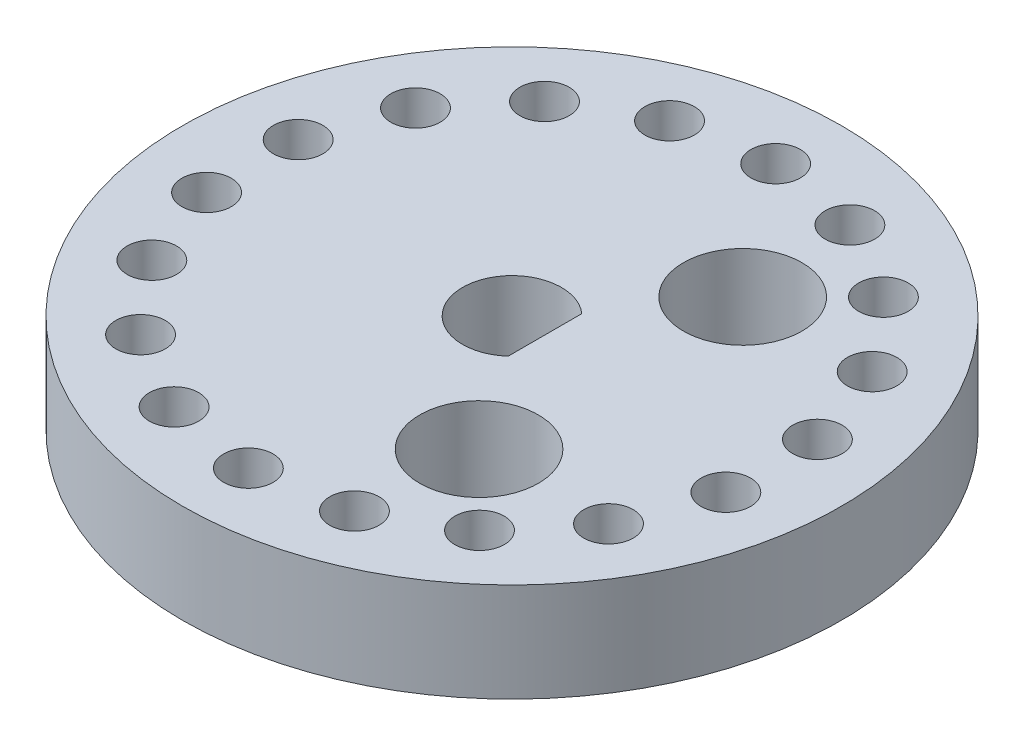
SolidWorks part; units mm, degrees
ref_plane "前视基准面" through (0, 0, 0) normal (0, 0, 1) x (1, 0, 0)
ref_plane "上视基准面" through (0, 0, 0) normal (0, 1, 0) x (1, 0, 0)
ref_plane "右视基准面" through (0, 0, 0) normal (1, 0, 0) x (0, 0, -1)
sketch "草图1" plane through (0, 0, 0) normal (0, 1, 0) x (1, 0, 0)
  circle A0 centre (0, 0) radius 10
extrude "凸台-拉伸1" add sketch "草图1" along normal blind 3
sketch "草图2" plane through (0, 3, 0) normal (0, 1, 0) x (1, 0, 0)
  line L0 (1, -1.118) -> (1, 1.118)
  line L20 (0, 0) -> (0, 1.25) construction
  arc A2 (1, -1.118) -> (1, 1.118) centre (0, 0) cw
  point P7 (0, 0)
  point P30 (0, 0)
sketch "草图3" plane through (0, 3, 0) normal (0, 1, 0) x (1, 0, 0)
  circle A19 centre (0, 0) radius 8 construction
  circle A39 centre (0, 8) radius 0.75
  circle A40 centre (2.7362, 7.5175) radius 0.75
  circle A63 centre (5.1423, 6.1284) radius 0.75
  circle A64 centre (6.9282, 4) radius 0.75
  circle A65 centre (7.8785, 1.3892) radius 0.75
  circle A66 centre (7.8785, -1.3892) radius 0.75
  circle A67 centre (6.9282, -4) radius 0.75
  circle A68 centre (5.1423, -6.1284) radius 0.75
  circle A69 centre (2.7362, -7.5175) radius 0.75
  circle A70 centre (0, -8) radius 0.75
  circle A71 centre (-2.7362, -7.5175) radius 0.75
  circle A72 centre (-5.1423, -6.1284) radius 0.75
  circle A73 centre (-6.9282, -4) radius 0.75
  circle A74 centre (-7.8785, -1.3892) radius 0.75
  circle A75 centre (-7.8785, 1.3892) radius 0.75
  circle A76 centre (-6.9282, 4) radius 0.75
  circle A77 centre (-5.1423, 6.1284) radius 0.75
  circle A78 centre (-2.7362, 7.5175) radius 0.75
  point P41 (0, 0)
  point P42 (0, 0)
  point P43 (0, 0)
  point P79 (0, 0)
  dimension "D1" = 18
extrude "切除-拉伸2" cut sketch "草图3" against normal through all
sketch "草图4" plane through (0, 3, 0) normal (0, 1, 0) x (1, 0, 0)
  line L2 (-10, 0) -> (10, 0) construction
  line L3 (0, 0) -> (3, 0) construction
  line L4 (3, 0) -> (3, -4) construction
  circle A3 centre (3, -4) radius 1.8
  circle A4 centre (3, 4) radius 1.8
extrude "切除-拉伸3" cut sketch "草图4" against normal through all
extrude "切除-拉伸6" cut sketch "草图2" against normal up to next
